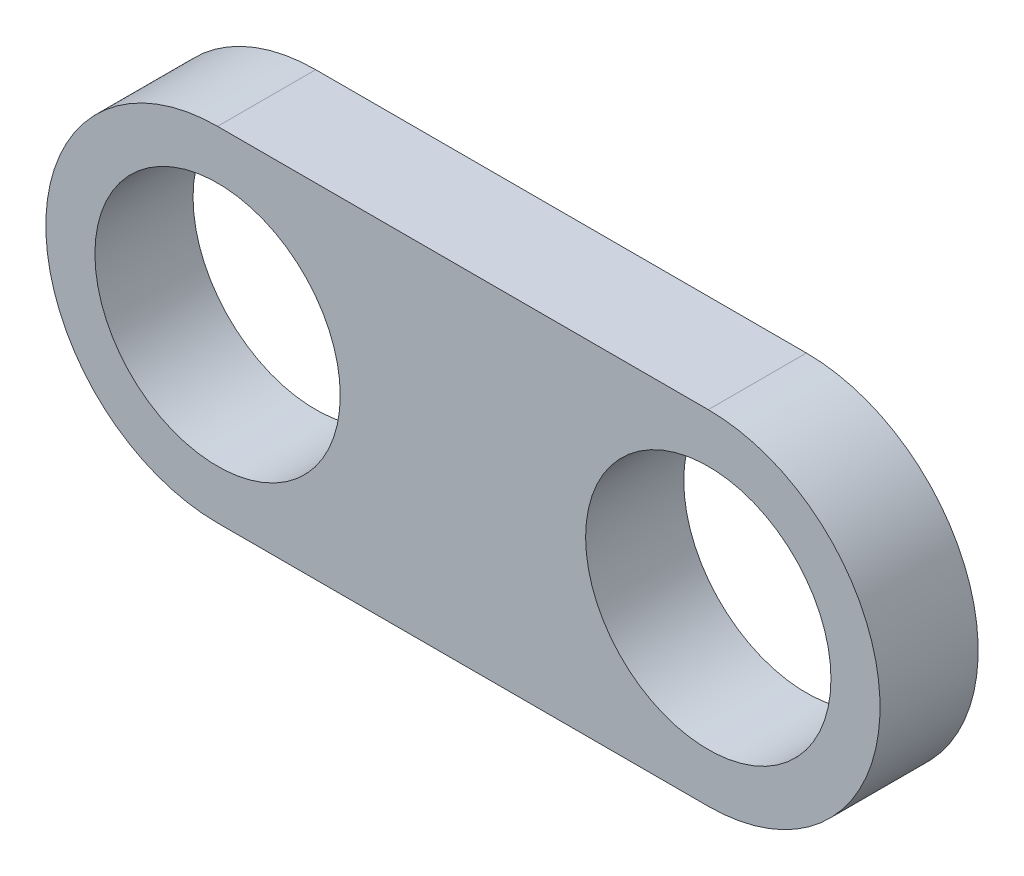
SolidWorks part; units mm, degrees
ref_plane "Спереди" through (0, 0, 0) normal (0, 0, 1) x (1, 0, 0)
ref_plane "Сверху" through (0, 0, 0) normal (0, 1, 0) x (1, 0, 0)
ref_plane "Справа" through (0, 0, 0) normal (1, 0, 0) x (0, 0, -1)
sketch "Эскиз1" plane through (0, 0, 0) normal (0, 0, 1) x (1, 0, 0)
  line L0 (0, 0) -> (100, 0) construction
  line L1 (0, 35) -> (100, 35)
  line L2 (0, -35) -> (100, -35)
  arc A0 (0, 35) -> (0, -35) centre (0, 0) ccw
  arc A1 (100, -35) -> (100, 35) centre (100, 0) ccw
  circle A2 centre (0, 0) radius 25
  circle A3 centre (100, 0) radius 25
  point P3 (50, 0)
  dimension "D1" = 100
extrude "Бобышка-Вытянуть1" add sketch "Эскиз1" along normal blind 20
